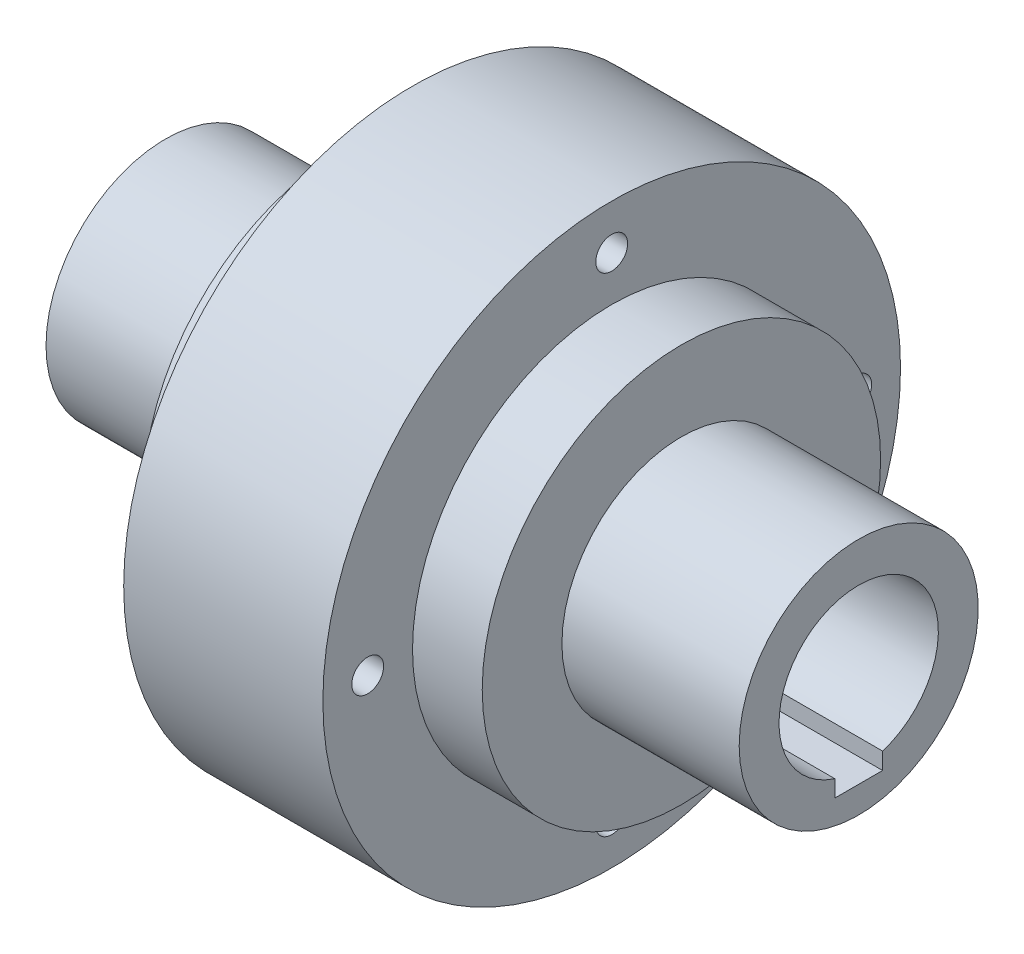
SolidWorks part; units mm, degrees
ref_plane "Спереди" through (0, 0, 0) normal (0, 0, 1) x (1, 0, 0)
ref_plane "Сверху" through (0, 0, 0) normal (0, 1, 0) x (1, 0, 0)
ref_plane "Справа" through (0, 0, 0) normal (1, 0, 0) x (0, 0, -1)
sketch "Эскиз1" plane through (0, 0, 0) normal (0, 0, 1) x (1, 0, 0)
  line L0 (-171.1041, 0) -> (197.3502, 0) construction
  line L1 (-5, 20) -> (-5, 30)
  line L2 (-5, 30) -> (-41.5, 30)
  line L3 (-41.5, 30) -> (-41.5, 40.0162)
  line L4 (-41.5, 40.0162) -> (41.5, 40.0162)
  line L6 (25, 72.5) -> (-25, 72.5)
  line L7 (-25, 72.5) -> (-25, 50)
  line L8 (-25, 50) -> (-42.5, 50)
  line L14 (-87, 20) -> (-5, 20)
  line L18 (-87, 20) -> (-87, 30)
  line L19 (-87, 30) -> (-42.5, 30)
  line L23 (-42.5, 50) -> (-42.5, 30)
  line L26 (0, 72.5) -> (0, -67.2144) construction
  line L29 (42.5, 50) -> (42.5, 30)
  line L30 (87, 30) -> (42.5, 30)
  line L31 (87, 20) -> (87, 30)
  line L32 (87, 20) -> (5, 20)
  line L33 (25, 50) -> (42.5, 50)
  line L34 (25, 72.5) -> (25, 50)
  line L35 (41.5, 30) -> (41.5, 40.0162)
  line L36 (5, 30) -> (41.5, 30)
  line L37 (5, 20) -> (5, 30)
  dimension "D1" = 100
  dimension "D2" = 10.0162
  dimension "D3" = 60
  dimension "D4" = 1
  dimension "D5" = 85
  dimension "dmin" = 40
  dimension "D" = 145
  dimension "L" = 174
  dimension "B" = 50
  dimension "lmin" = 82
revolve "Повернуть1" add sketch "Эскиз1" angle 360 about L0
sketch "Эскиз2" plane through (25, 0, 0) normal (1, 0, 0) x (0, 0, -1)
  circle A0 centre (0, 61.25) radius 4
  dimension "D1" = 8
  dimension "D2" = 61.25
extrude "Вырез-Вытянуть1" cut sketch "Эскиз2" against normal through all
pattern_circular "Круговой массив1" count 4 over 360 about axis through (0, 0, 0) along (1, 0, 0) of "Вырез-Вытянуть1"
sketch "Эскиз4" plane through (-87, 0, 0) normal (-1, 0, 0) x (0, 0, 1)
  line L1 (-6, 0) -> (6, 0)
  line L2 (-6, 0) -> (-6, -23.3)
  line L3 (-6, -23.3) -> (6, -23.3)
  line L4 (6, 0) -> (6, -23.3)
  dimension "D1" = 23.3
  dimension "D2" = 12
extrude "Вырез-Вытянуть2" cut sketch "Эскиз4" against normal through all
